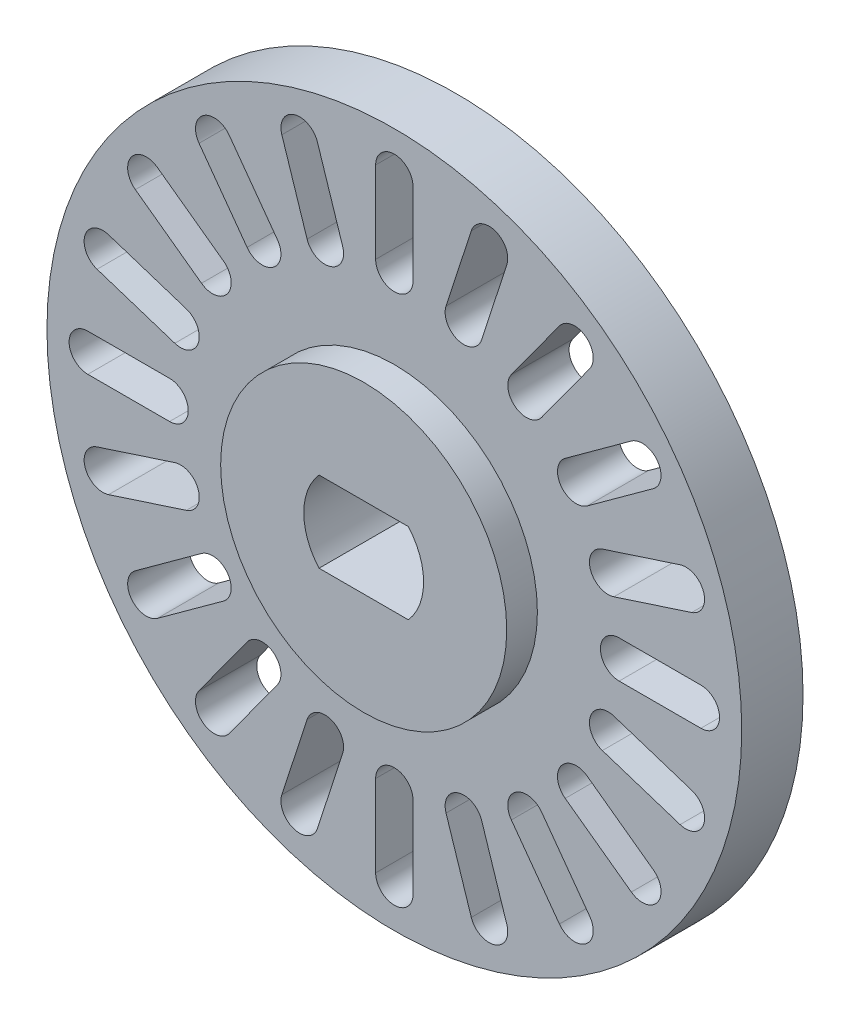
SolidWorks part; units mm, degrees
ref_plane "Front Plane" through (0, 0, 0) normal (0, 0, 1) x (1, 0, 0)
ref_plane "Top Plane" through (0, 0, 0) normal (0, 1, 0) x (1, 0, 0)
ref_plane "Right Plane" through (0, 0, 0) normal (1, 0, 0) x (0, 0, -1)
sketch "Sketch3" plane through (0, 0, 0) normal (0, 0, 1) x (-1, 0, 0)
  line L0 (-2.185, 1.975) -> (2.185, 1.975)
  line L1 (-2.185, -1.975) -> (2.185, -1.975)
  line L2 (-2.185, -1.975) -> (-2.01, -1.8) construction
  line L3 (2.01, -1.8) -> (2.185, -1.975) construction
  line L4 (2.01, 1.8) -> (2.185, 1.975) construction
  line L5 (-2.01, 1.8) -> (-2.185, 1.975) construction
  line L6 (2.185, 1.975) -> (2.185, 1.8) construction
  line L7 (2.185, 1.8) -> (2.01, 1.8) construction
  line L8 (2.01, -1.8) -> (2.185, -1.8) construction
  line L9 (2.185, -1.8) -> (2.185, -1.975) construction
  arc A0 (2.185, 1.975) -> (2.185, -1.975) centre (-0.0525, 0) cw
  arc A1 (-2.185, -1.975) -> (-2.185, 1.975) centre (0.0525, 0) cw
  point P14 (0, 0)
sketch "Sketch4" plane through (0, 0, 0) normal (0, 0, 1) x (1, 0, 0)
  circle A0 centre (0, 0) radius 17
  dimension "D1" = 34
extrude "Boss-Extrude2" add sketch "Sketch4" along normal blind 3
sketch "Sketch5" plane through (0, 0, 3) normal (0, 0, 1) x (1, 0, 0)
  circle A0 centre (0, 0) radius 7
  point P0 (0, 0)
  dimension "D1" = 14
extrude "Boss-Extrude3" add sketch "Sketch5" along normal blind 1.5
extrude "Cut-Extrude2" cut sketch "Sketch3" along normal through all
sketch "Sketch6" plane through (0, 0, 3) normal (0, 0, 1) x (1, 0, 0)
  line L0 (11, 0) -> (15, 0) construction
  line L1 (11, 0.9148) -> (15, 0.9148)
  line L2 (11, -0.9148) -> (15, -0.9148)
  line L3 (10.4616, -3.3992) -> (14.2658, -4.6353) construction
  line L4 (10.7443, -2.5292) -> (14.5485, -3.7652)
  line L5 (10.1789, -4.2692) -> (13.9832, -5.5053)
  line L6 (8.8992, -6.4656) -> (12.1353, -8.8168) construction
  line L7 (9.4369, -5.7255) -> (12.673, -8.0767)
  line L8 (8.3615, -7.2057) -> (11.5975, -9.5569)
  line L9 (6.4656, -8.8992) -> (8.8168, -12.1353) construction
  line L10 (7.2057, -8.3615) -> (9.5569, -11.5975)
  line L11 (5.7255, -9.4369) -> (8.0767, -12.673)
  line L12 (3.3992, -10.4616) -> (4.6353, -14.2658) construction
  line L13 (4.2692, -10.1789) -> (5.5053, -13.9832)
  line L14 (2.5292, -10.7443) -> (3.7652, -14.5485)
  line L15 (0, -11) -> (0, -15) construction
  line L16 (0.9148, -11) -> (0.9148, -15)
  line L17 (-0.9148, -11) -> (-0.9148, -15)
  line L18 (-3.3992, -10.4616) -> (-4.6353, -14.2658) construction
  line L19 (-2.5292, -10.7443) -> (-3.7652, -14.5485)
  line L20 (-4.2692, -10.1789) -> (-5.5053, -13.9832)
  line L21 (-6.4656, -8.8992) -> (-8.8168, -12.1353) construction
  line L22 (-5.7255, -9.4369) -> (-8.0767, -12.673)
  line L23 (-7.2057, -8.3615) -> (-9.5569, -11.5975)
  line L24 (-8.8992, -6.4656) -> (-12.1353, -8.8168) construction
  line L25 (-8.3615, -7.2057) -> (-11.5975, -9.5569)
  line L26 (-9.4369, -5.7255) -> (-12.673, -8.0767)
  line L27 (-10.4616, -3.3992) -> (-14.2658, -4.6353) construction
  line L28 (-10.1789, -4.2692) -> (-13.9832, -5.5053)
  line L29 (-10.7443, -2.5292) -> (-14.5485, -3.7652)
  line L30 (-11, 0) -> (-15, 0) construction
  line L31 (-11, -0.9148) -> (-15, -0.9148)
  line L32 (-11, 0.9148) -> (-15, 0.9148)
  line L33 (-10.4616, 3.3992) -> (-14.2658, 4.6353) construction
  line L34 (-10.7443, 2.5292) -> (-14.5485, 3.7652)
  line L35 (-10.1789, 4.2692) -> (-13.9832, 5.5053)
  line L36 (-8.8992, 6.4656) -> (-12.1353, 8.8168) construction
  line L37 (-9.4369, 5.7255) -> (-12.673, 8.0767)
  line L38 (-8.3615, 7.2057) -> (-11.5975, 9.5569)
  line L39 (-6.4656, 8.8992) -> (-8.8168, 12.1353) construction
  line L40 (-7.2057, 8.3615) -> (-9.5569, 11.5975)
  line L41 (-5.7255, 9.4369) -> (-8.0767, 12.673)
  line L42 (-3.3992, 10.4616) -> (-4.6353, 14.2658) construction
  line L43 (-4.2692, 10.1789) -> (-5.5053, 13.9832)
  line L44 (-2.5292, 10.7443) -> (-3.7652, 14.5485)
  line L45 (0, 11) -> (0, 15) construction
  line L46 (-0.9148, 11) -> (-0.9148, 15)
  line L47 (0.9148, 11) -> (0.9148, 15)
  line L48 (3.3992, 10.4616) -> (4.6353, 14.2658) construction
  line L49 (2.5292, 10.7443) -> (3.7652, 14.5485)
  line L50 (4.2692, 10.1789) -> (5.5053, 13.9832)
  line L51 (6.4656, 8.8992) -> (8.8168, 12.1353) construction
  line L52 (5.7255, 9.4369) -> (8.0767, 12.673)
  line L53 (7.2057, 8.3615) -> (9.5569, 11.5975)
  line L54 (8.8992, 6.4656) -> (12.1353, 8.8168) construction
  line L55 (8.3615, 7.2057) -> (11.5975, 9.5569)
  line L56 (9.4369, 5.7255) -> (12.673, 8.0767)
  line L57 (10.4616, 3.3992) -> (14.2658, 4.6353) construction
  line L58 (10.1789, 4.2692) -> (13.9832, 5.5053)
  line L59 (10.7443, 2.5292) -> (14.5485, 3.7652)
  arc A0 (11, 0.9148) -> (11, -0.9148) centre (11, 0) ccw
  arc A1 (15, -0.9148) -> (15, 0.9148) centre (15, 0) ccw
  arc A3 (10.7443, -2.5292) -> (10.1789, -4.2692) centre (10.4616, -3.3992) ccw
  arc A4 (13.9832, -5.5053) -> (14.5485, -3.7652) centre (14.2658, -4.6353) ccw
  arc A5 (9.4369, -5.7255) -> (8.3615, -7.2057) centre (8.8992, -6.4656) ccw
  arc A6 (11.5975, -9.5569) -> (12.673, -8.0767) centre (12.1353, -8.8168) ccw
  arc A7 (7.2057, -8.3615) -> (5.7255, -9.4369) centre (6.4656, -8.8992) ccw
  arc A8 (8.0767, -12.673) -> (9.5569, -11.5975) centre (8.8168, -12.1353) ccw
  arc A9 (4.2692, -10.1789) -> (2.5292, -10.7443) centre (3.3992, -10.4616) ccw
  arc A10 (3.7652, -14.5485) -> (5.5053, -13.9832) centre (4.6353, -14.2658) ccw
  arc A11 (0.9148, -11) -> (-0.9148, -11) centre (0, -11) ccw
  arc A12 (-0.9148, -15) -> (0.9148, -15) centre (0, -15) ccw
  arc A13 (-2.5292, -10.7443) -> (-4.2692, -10.1789) centre (-3.3992, -10.4616) ccw
  arc A14 (-5.5053, -13.9832) -> (-3.7652, -14.5485) centre (-4.6353, -14.2658) ccw
  arc A15 (-5.7255, -9.4369) -> (-7.2057, -8.3615) centre (-6.4656, -8.8992) ccw
  arc A16 (-9.5569, -11.5975) -> (-8.0767, -12.673) centre (-8.8168, -12.1353) ccw
  arc A17 (-8.3615, -7.2057) -> (-9.4369, -5.7255) centre (-8.8992, -6.4656) ccw
  arc A18 (-12.673, -8.0767) -> (-11.5975, -9.5569) centre (-12.1353, -8.8168) ccw
  arc A19 (-10.1789, -4.2692) -> (-10.7443, -2.5292) centre (-10.4616, -3.3992) ccw
  arc A20 (-14.5485, -3.7652) -> (-13.9832, -5.5053) centre (-14.2658, -4.6353) ccw
  arc A21 (-11, -0.9148) -> (-11, 0.9148) centre (-11, 0) ccw
  arc A22 (-15, 0.9148) -> (-15, -0.9148) centre (-15, 0) ccw
  arc A23 (-10.7443, 2.5292) -> (-10.1789, 4.2692) centre (-10.4616, 3.3992) ccw
  arc A24 (-13.9832, 5.5053) -> (-14.5485, 3.7652) centre (-14.2658, 4.6353) ccw
  arc A25 (-9.4369, 5.7255) -> (-8.3615, 7.2057) centre (-8.8992, 6.4656) ccw
  arc A26 (-11.5975, 9.5569) -> (-12.673, 8.0767) centre (-12.1353, 8.8168) ccw
  arc A27 (-7.2057, 8.3615) -> (-5.7255, 9.4369) centre (-6.4656, 8.8992) ccw
  arc A28 (-8.0767, 12.673) -> (-9.5569, 11.5975) centre (-8.8168, 12.1353) ccw
  arc A29 (-4.2692, 10.1789) -> (-2.5292, 10.7443) centre (-3.3992, 10.4616) ccw
  arc A30 (-3.7652, 14.5485) -> (-5.5053, 13.9832) centre (-4.6353, 14.2658) ccw
  arc A31 (-0.9148, 11) -> (0.9148, 11) centre (0, 11) ccw
  arc A32 (0.9148, 15) -> (-0.9148, 15) centre (0, 15) ccw
  arc A33 (2.5292, 10.7443) -> (4.2692, 10.1789) centre (3.3992, 10.4616) ccw
  arc A34 (5.5053, 13.9832) -> (3.7652, 14.5485) centre (4.6353, 14.2658) ccw
  arc A35 (5.7255, 9.4369) -> (7.2057, 8.3615) centre (6.4656, 8.8992) ccw
  arc A36 (9.5569, 11.5975) -> (8.0767, 12.673) centre (8.8168, 12.1353) ccw
  arc A37 (8.3615, 7.2057) -> (9.4369, 5.7255) centre (8.8992, 6.4656) ccw
  arc A38 (12.673, 8.0767) -> (11.5975, 9.5569) centre (12.1353, 8.8168) ccw
  arc A39 (10.1789, 4.2692) -> (10.7443, 2.5292) centre (10.4616, 3.3992) ccw
  arc A40 (14.5485, 3.7652) -> (13.9832, 5.5053) centre (14.2658, 4.6353) ccw
  point P3 (13, 0)
  point P12 (12.3637, -4.0172)
  point P19 (10.5172, -7.6412)
  point P26 (7.6412, -10.5172)
  point P33 (4.0172, -12.3637)
  point P40 (0, -13)
  point P47 (-4.0172, -12.3637)
  point P54 (-7.6412, -10.5172)
  point P61 (-10.5172, -7.6412)
  point P68 (-12.3637, -4.0172)
  point P75 (-13, 0)
  point P82 (-12.3637, 4.0172)
  point P89 (-10.5172, 7.6412)
  point P96 (-7.6412, 10.5172)
  point P103 (-4.0172, 12.3637)
  point P110 (0, 13)
  point P117 (4.0172, 12.3637)
  point P124 (7.6412, 10.5172)
  point P131 (10.5172, 7.6412)
  point P138 (12.3637, 4.0172)
  point P143 (0, 0)
  dimension "D1" = 4
  dimension "D2" = 13
  dimension "D3" = 20
extrude "Cut-Extrude3" cut sketch "Sketch6" against normal through all
